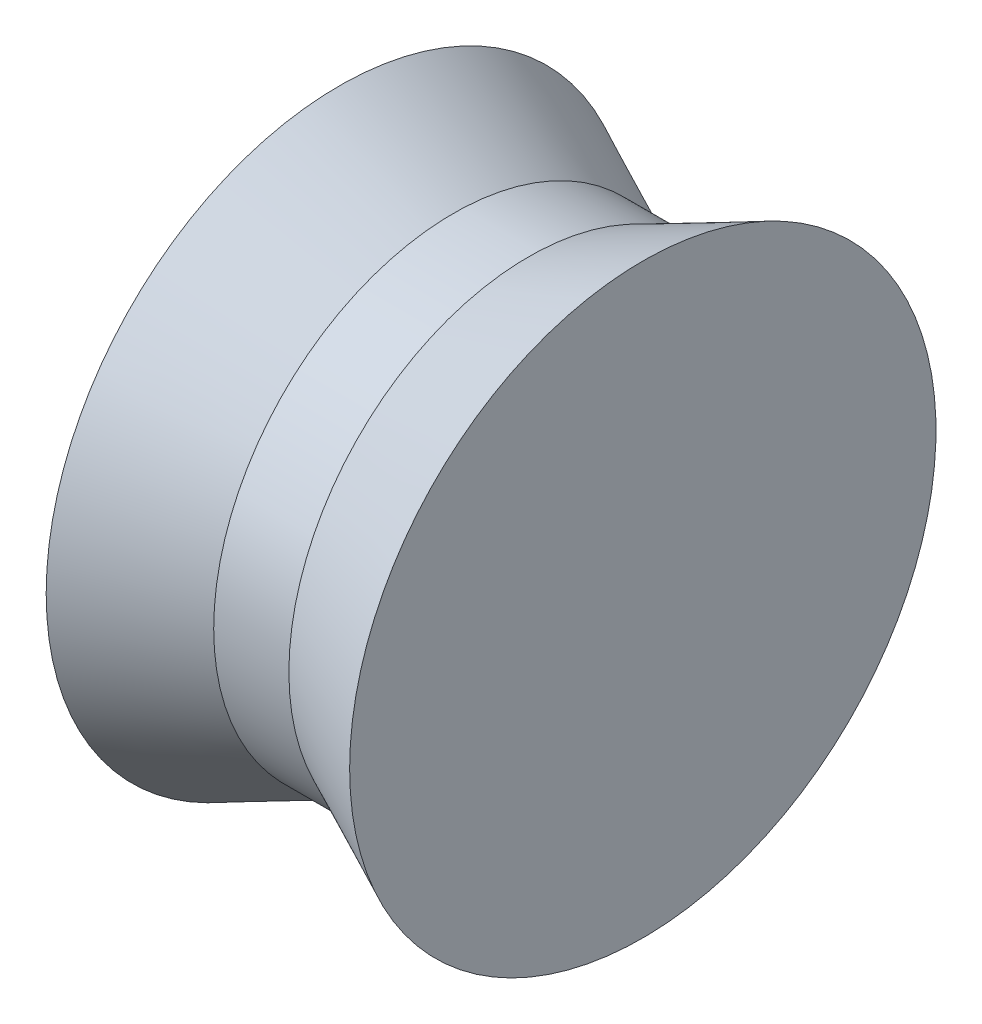
SolidWorks part; units mm, degrees
ref_plane "Front Plane" through (0, 0, 0) normal (0, 0, 1) x (1, 0, 0)
ref_plane "Top Plane" through (0, 0, 0) normal (0, 1, 0) x (1, 0, 0)
ref_plane "Right Plane" through (0, 0, 0) normal (1, 0, 0) x (0, 0, -1)
sketch "Sketch1" plane through (0, 0, 0) normal (0, 0, 1) x (1, 0, 0)
  line L0 (-25.125, 0) -> (25.125, 0)
  line L1 (25.125, 0) -> (25.125, 48.5496)
  line L2 (25.125, 48.5496) -> (6.2255, 39.7102)
  line L3 (6.2255, 39.7102) -> (-6.2255, 39.7102)
  line L4 (-6.2255, 39.7102) -> (-25.125, 48.5496)
  line L5 (-25.125, 48.5496) -> (-25.125, 0)
  point P4 (0, 39.7102)
  point P8 (0, 0)
  point P9 (7.1709, 47.065)
  point P10 (27.7958, 54.0903)
  point P11 (6.2255, 39.7102)
  point P12 (25.125, 48.5496)
revolve "Revolve1" add sketch "Sketch1" angle 360 about L0
